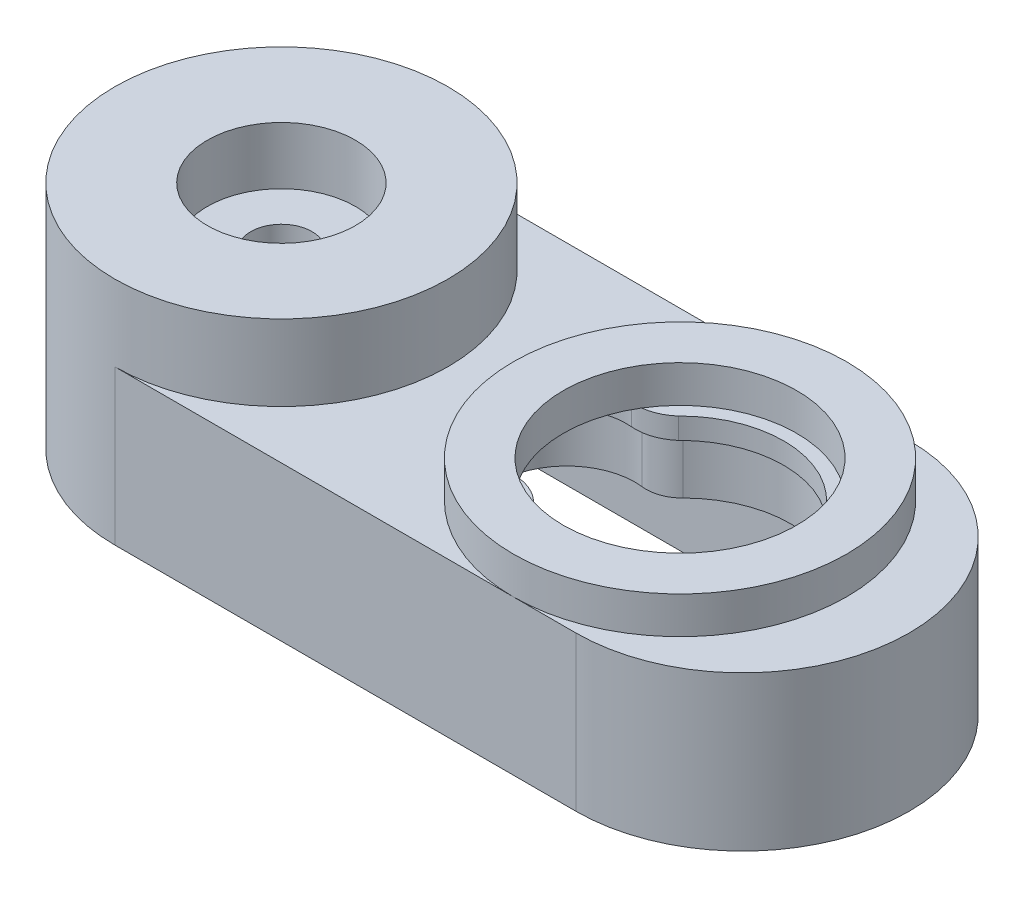
SolidWorks part; units mm, degrees
ref_plane "前视基准面" through (0, 0, 0) normal (0, 0, 1) x (1, 0, 0)
ref_plane "上视基准面" through (0, 0, 0) normal (0, 1, 0) x (1, 0, 0)
ref_plane "右视基准面" through (0, 0, 0) normal (1, 0, 0) x (0, 0, -1)
other "Configuration Table"
sketch "草图1" plane through (0, 0, 0) normal (0, 1, 0) x (1, 0, 0)
  line L0 (0, 0) -> (11.8, 0) construction
  line L1 (-11.8, 6) -> (11.8, 6)
  line L2 (-11.8, 6) -> (-11.8, -6)
  line L3 (-11.8, -6) -> (11.8, -6)
  line L4 (11.8, 6) -> (11.8, -6)
  line L5 (-11.8, 6) -> (11.8, -6) construction
  line L6 (-11.8, -6) -> (11.8, 6) construction
  line L7 (0, 0) -> (-0.28, 0) construction
  arc A1 (0.0075, 3.2875) -> (0.0075, -3.2875) centre (-0.28, 0) ccw
  arc A3 (0.0075, -3.2875) -> (1.9157, -3.9147) centre (0.2296, -5.8278) cw
  arc A4 (0.0075, 3.2875) -> (1.9157, 3.9147) centre (0.2296, 5.8278) ccw
  arc A5 (1.9157, -3.9147) -> (1.9157, 3.9147) centre (5.92, 0) ccw
  point P0 (0, 0)
  dimension "D5" = 6.6
  dimension "D6" = 5.6
  dimension "D7" = 2.55
  dimension "D1" = 12
  dimension "D2" = 23.6
  dimension "D3" = 5.88
  dimension "D4" = 6.2
extrude "凸台-拉伸1" add sketch "草图1" against normal blind 1.14
sketch "草图2" plane through (0, -1.14, 0) normal (0, -1, 0) x (1, 0, 0)
  line L0 (-0.28, 0) -> (5.92, 0) construction
  line L1 (11.8, 6) -> (11.8, -6) construction
  line L2 (11.8, -6) -> (-11.8, -6) construction
  line L3 (-11.8, 6) -> (11.8, 6) construction
  line L4 (-11.8, -6) -> (-11.8, 6) construction
  line L5 (11.8, 6) -> (11.8, -6)
  line L6 (11.8, -6) -> (-11.8, -6)
  line L7 (-11.8, 6) -> (11.8, 6)
  line L8 (-11.8, -6) -> (-11.8, 6)
  arc A1 (1.859, -4.2108) -> (1.859, 4.2108) centre (5.92, 0) ccw
  arc A2 (0.2072, 3.6678) -> (0.2072, -3.6678) centre (-0.28, 0) ccw
  arc A3 (0.2072, -3.6678) -> (1.859, -4.2108) centre (0.4706, -5.6504) cw
  arc A4 (0.2072, 3.6678) -> (1.859, 4.2108) centre (0.4706, 5.6504) ccw
  dimension "D1" = 11.7
  dimension "D2" = 7.4
  dimension "D3" = 2
extrude "凸台-拉伸2" add sketch "草图2" along normal blind 3.2
sketch "草图3" plane through (0, 0, 6) normal (0, 0, 1) x (1, 0, 0)
  line L0 (-11.8, -4.34) -> (-11, -4.34)
  line L1 (11.8, -4.34) -> (-11.8, -4.34) construction
  line L2 (-11, -4.34) -> (-10.8939, -4.2339)
  line L3 (-10.8939, -4.2339) -> (10.9027, -3.8535)
  line L4 (10.9027, -3.8535) -> (11.2209, -4.1717)
  line L5 (11.2209, -4.1717) -> (11.2209, -4.34)
  line L6 (11.2209, -4.34) -> (-11, -4.34)
  line M7 (-11.8, -4.34) -> (11.8, -4.34)
  dimension "D1" = 0.8
  dimension "D2" = 136
  dimension "D3" = 0.15
  dimension "D4" = 45
  dimension "D5" = 21.8
  dimension "D6" = 0.45
extrude "切除-拉伸1" cut sketch "草图3" against normal through all contours L5 L4 L3 L2 M7
sketch "草图4" plane through (0, 0, 6) normal (0, 0, 1) x (1, 0, 0)
  line L0 (-11.8, -4.34) -> (-11.8, -8.34)
  line L1 (-11.8, -8.34) -> (11.8, -8.34)
  line L2 (11.8, -8.34) -> (11.8, -4.34)
  line L9 (10.9027, -3.8535) -> (11.2209, -4.1717)
  line L10 (11.2209, -4.1717) -> (11.2209, -4.34)
  line L11 (11.2209, -4.34) -> (11.8, -4.34)
  line L12 (11.8, -4.34) -> (11.8, 0)
  line L13 (11.8, 0) -> (-11.8, 0)
  line L14 (-11.8, 0) -> (-11.8, -4.34)
  line L15 (-11.8, -4.34) -> (-11, -4.34)
  line L16 (-11, -4.34) -> (-10.8939, -4.2339)
  line L17 (-10.8939, -4.2339) -> (10.9027, -3.8535)
  line L21 (11.8, -4.34) -> (11.8, 0)
  line L22 (11.8, 0) -> (-11.8, 0)
  line L23 (-11.8, 0) -> (-11.8, -4.34)
  dimension "D2" = 4
  dimension "D1" = 0
extrude "凸台-拉伸3" add sketch "草图4" along normal blind 3
sketch "草图5" plane through (0, 0, -6) normal (0, 0, -1) x (-1, 0, 0)
  line L0 (11.8, -8.34) -> (-11.8, -8.34) construction
  line L1 (11.8, -4.34) -> (11.8, -8.34) construction
  line L2 (11.8, -4.34) -> (11.8, 0) construction
  line L3 (-11.8, 0) -> (11.8, 0) construction
  line L4 (-11.8, -4.34) -> (-11.8, 0) construction
  line L5 (-11.8, -8.34) -> (-11.8, -4.34) construction
  line L6 (11.8, -8.34) -> (-11.8, -8.34)
  line L7 (11.8, -4.34) -> (11.8, -8.34)
  line L8 (11.8, -4.34) -> (11.8, 0)
  line L9 (-11.8, 0) -> (11.8, 0)
  line L10 (-11.8, -4.34) -> (-11.8, 0)
  line L11 (-11.8, -8.34) -> (-11.8, -4.34)
extrude "凸台-拉伸4" add sketch "草图5" along normal blind 3
sketch "草图6" plane through (0, 0, 0) normal (0, 1, 0) x (1, 0, 0)
  line L0 (11.8, -9) -> (16.3, -9)
  line L1 (16.3, -9) -> (16.3, 9)
  line L2 (16.3, 9) -> (11.8, 9)
  line L3 (11.8, 9) -> (11.8, -9)
  line L4 (11.8, 0) -> (16.3, 0) construction
  line L5 (0, 9) -> (0, -9) construction
  line L6 (-11.8, 9) -> (11.8, 9) construction
  line L7 (11.8, -9) -> (-11.8, -9) construction
  line L8 (-11.8, 0) -> (-16.3, 0) construction
  line L9 (-11.8, 9) -> (-11.8, -9)
  line L10 (-16.3, 9) -> (-11.8, 9)
  line L11 (-16.3, -9) -> (-16.3, 9)
  line L12 (-11.8, -9) -> (-16.3, -9)
  dimension "D3" = 4.5
extrude "凸台-拉伸6" add sketch "草图6" along normal blind 6 from offset 8.34 offset against normal yes
sketch "草图9" plane through (-16.3, 0, 0) normal (-1, 0, 0) x (0, 0, 1)
  line L4 (-9, -8.34) -> (9, -8.34)
  line L5 (9, -8.34) -> (9, -2.34)
  line L6 (9, -2.34) -> (-9, -2.34)
  line L7 (-9, -2.34) -> (-9, -8.34)
  line L8 (-9, -8.34) -> (9, -8.34)
  line L9 (9, -8.34) -> (9, -2.34)
  line L10 (9, -2.34) -> (-9, -2.34)
  line L11 (-9, -2.34) -> (-9, -8.34)
  dimension "D1" = 0
extrude "凸台-拉伸8" add sketch "草图9" along normal blind 4
sketch "草图11" plane through (0, -2.34, 0) normal (0, 1, 0) x (1, 0, 0)
  line L4 (-11.8, 9) -> (-20.3, 9)
  line L5 (-20.3, 9) -> (-20.3, -9)
  line L6 (-20.3, -9) -> (-11.8, -9)
  line L7 (-11.8, -9) -> (-11.8, 9)
  line L8 (-11.8, 9) -> (-20.3, 9)
  line L9 (-20.3, 9) -> (-20.3, -9)
  line L10 (-20.3, -9) -> (-11.8, -9)
  line L11 (-11.8, -9) -> (-11.8, 9)
  dimension "D1" = 0
extrude "凸台-拉伸11" add sketch "草图11" along direction (0, 1, 0) on the side of the normal blind 2.34 contours L8 L9 L10 L11
sketch "草图12" plane through (0, 0, 0) normal (0, 1, 0) x (1, 0, 0)
  line L0 (-20.3, 0) -> (-15.61, 0) construction
  line L1 (-20.3, 9) -> (-20.3, -9) construction
  line L2 (-20.3, 9) -> (11.8, 9) construction
  line L9 (-20.3, 9) -> (11.8, 9) construction
  circle A0 centre (-15.61, 0) radius 1.65
  dimension "D2" = 3.3
  dimension "D1" = 4.69
sketch "草图13" plane through (16.3, 0, 0) normal (1, 0, 0) x (0, 0, -1)
  line L4 (-9, -8.34) -> (9, -8.34)
  line L5 (9, -8.34) -> (9, -2.34)
  line L6 (9, -2.34) -> (-9, -2.34)
  line L7 (-9, -2.34) -> (-9, -8.34)
  line L8 (-9, -8.34) -> (9, -8.34)
  line L9 (9, -8.34) -> (9, -2.34)
  line L10 (9, -2.34) -> (-9, -2.34)
  line L11 (-9, -2.34) -> (-9, -8.34)
  dimension "D1" = 0
extrude "凸台-拉伸12" add sketch "草图13" along normal blind 2
sketch "草图14" plane through (-20.3, 0, 0) normal (-1, 0, 0) x (0, 0, 1)
  line L4 (-9, 0) -> (-9, -8.34)
  line L5 (-9, -8.34) -> (9, -8.34)
  line L6 (9, -8.34) -> (9, 0)
  line L7 (9, 0) -> (-9, 0)
  line L8 (-9, 0) -> (-9, -8.34)
  line L9 (-9, -8.34) -> (9, -8.34)
  line L10 (9, -8.34) -> (9, 0)
  line L11 (9, 0) -> (-9, 0)
  dimension "D1" = 0
extrude "凸台-拉伸13" add sketch "草图14" along normal blind 8
sketch "草图15" plane through (0, -2.34, 0) normal (0, 1, 0) x (1, 0, 0)
  line L4 (11.8, 9) -> (11.8, -9)
  line L5 (11.8, -9) -> (18.3, -9)
  line L6 (18.3, -9) -> (18.3, 9)
  line L7 (18.3, 9) -> (11.8, 9)
  line L8 (11.8, 9) -> (11.8, -9)
  line L9 (11.8, -9) -> (18.3, -9)
  line L10 (18.3, -9) -> (18.3, 9)
  line L11 (18.3, 9) -> (11.8, 9)
  dimension "D1" = 0
extrude "凸台-拉伸14" add sketch "草图15" along normal up to surface (2.34 mm away) up to face at (2.498, 0, 0)
extrude "切除-拉伸2" cut sketch "草图12" against normal up to surface (8.34 mm away) up to face at (0, -8.34, 0)
sketch "草图16" plane through (0, -8.34, 0) normal (0, -1, 0) x (1, 0, 0)
  circle A0 centre (-15.61, 0) radius 3
  dimension "D1" = 6
extrude "切除-拉伸3" cut sketch "草图16" against normal blind 3
sketch "草图17" plane through (0, 0, 0) normal (0, 1, 0) x (1, 0, 0)
  circle A1 centre (5.92, 0) radius 9
  circle A2 centre (5.92, 0) radius 6.3039
extrude "凸台-拉伸15" add sketch "草图17" along normal blind 2
sketch "草图18" plane through (0, 0, 0) normal (0, 1, 0) x (1, 0, 0)
  circle A0 centre (-15.61, 0) radius 9
  dimension "D1" = 18
extrude "凸台-拉伸16" add sketch "草图18" along normal blind 1
sketch "草图19" plane through (0, 0, 0) normal (0, -1, 0) x (1, 0, 0)
  circle A1 centre (-15.61, 0) radius 1.65
  circle A2 centre (-15.61, 0) radius 1.65
  dimension "D1" = 0
extrude "切除-拉伸4" cut sketch "草图19" against normal blind 10
sketch "草图20" plane through (0, 0, 0) normal (0, 1, 0) x (1, 0, 0)
  line L0 (-15.61, -9) -> (-28.3, -9)
  line L1 (-28.3, -9) -> (-28.3, 9)
  line L2 (-28.3, 9) -> (-15.61, 9)
  arc A0 (-15.61, 9) -> (-15.61, -9) centre (-15.61, 0) ccw
extrude "切除-拉伸5" cut sketch "草图20" against normal up to surface (8.34 mm away) up to face at (-15.61, -8.34, -3)
sketch "草图21" plane through (0, 0, 0) normal (0, 1, 0) x (1, 0, 0)
  line L0 (18.3, -9) -> (18.3, 9) construction
  line L1 (9.3, -9) -> (18.3, -9)
  line L2 (18.3, -9) -> (18.3, 9)
  line L3 (18.3, 9) -> (12.11, 9)
  line L4 (5.92, 9) -> (18.3, 9) construction
  arc A0 (9.3, -9) -> (9.3, 9) centre (9.3, 0) ccw
  line M6 (5.92, -9) -> (18.3, -9)
  line M7 (18.3, -9) -> (18.3, 9)
  line M8 (18.3, 9) -> (5.92, 9)
extrude "切除-拉伸6" cut sketch "草图21" against normal up to surface (8.34 mm away) contours A0 L2 M8 | A0 M6 M7 up to face at (-15.61, -8.34, -3)
sketch "草图23" plane through (0, 1, 0) normal (0, 1, 0) x (1, 0, 0)
  circle A0 centre (-15.61, 0) radius 4
  circle A1 centre (-15.61, 0) radius 9
  circle M2 centre (-15.61, 0) radius 1.65
  dimension "D1" = 8
extrude "凸台-拉伸17" add sketch "草图23" along normal blind 3.1 contours M2 | A0 M2 | A1
